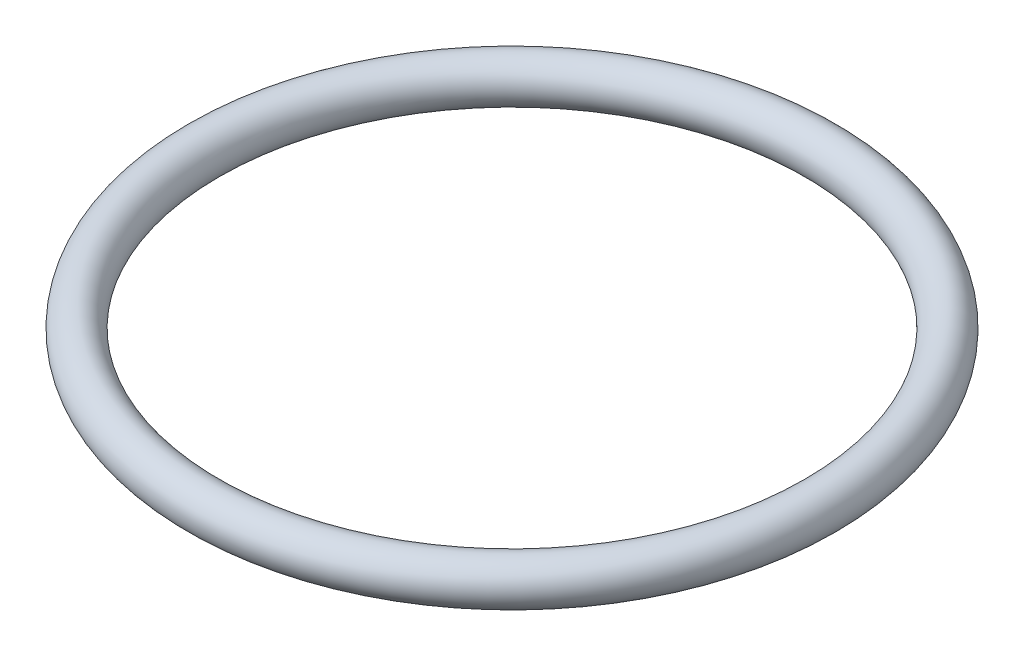
SolidWorks part; units mm, degrees
ref_plane "Front Plane" through (0, 0, 0) normal (0, 0, 1) x (1, 0, 0)
ref_plane "Top Plane" through (0, 0, 0) normal (0, 1, 0) x (1, 0, 0)
ref_plane "Right Plane" through (0, 0, 0) normal (1, 0, 0) x (0, 0, -1)
sketch "Sketch1" plane through (0, 0, 0) normal (0, 1, 0) x (1, 0, 0)
  line L0 (-361.95, 0) -> (361.95, 0) construction
  circle A0 centre (0, 0) radius 361.95
  point P4 (0, 0)
sketch "Sketch2" plane through (0, 0, 0) normal (0, 0, 1) x (1, 0, 0)
  line L0 (-361.95, 0) -> (361.95, 0) construction
  circle A0 centre (-361.95, 0) radius 25.4
  dimension "D1" = 50.8
sweep "Sweep1" add profiles "Sketch2" path "Sketch1"
